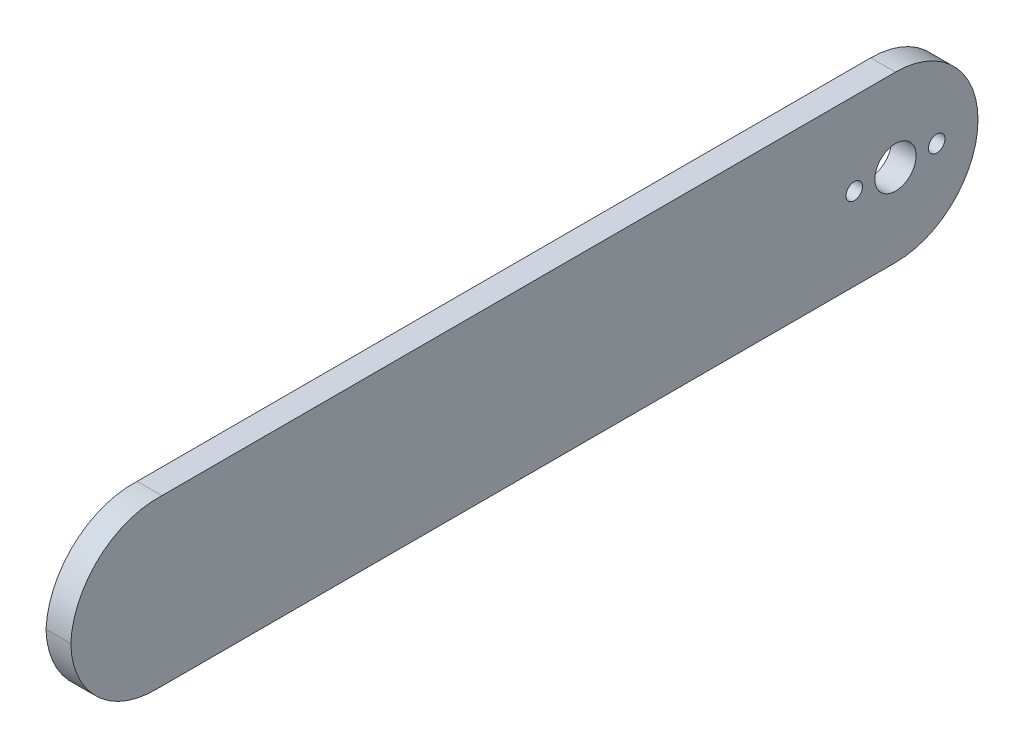
SolidWorks part; units mm, degrees
ref_plane "Front" through (0, 0, 0) normal (0, 0, 1) x (1, 0, 0)
ref_plane "Top" through (0, 0, 0) normal (0, 1, 0) x (1, 0, 0)
ref_plane "Right" through (0, 0, 0) normal (1, 0, 0) x (0, 0, -1)
sketch "Sketch1" plane through (0, 0, 0) normal (1, 0, 0) x (0, 0, -1)
  line L0 (-81.3717, 9.0404) -> (7.5758, 9.0404)
  line L1 (-81.898, -10.9596) -> (7.5758, -10.9596)
  arc A0 (17.5758, -0.9596) -> (7.5758, 9.0404) centre (7.5758, -0.9596) ccw
  arc A1 (7.5758, -10.9596) -> (17.5758, -0.9596) centre (7.5758, -0.9596) ccw
  arc A2 (-92.4242, -0.9596) -> (-81.3717, 9.0404) centre (-81.898, -1.4859) cw
  arc A3 (-81.898, -10.9596) -> (-92.4242, -0.9596) centre (-82.1611, -0.6965) cw
  circle A4 centre (7.5758, -0.9596) radius 2.5
  circle A5 centre (12.5758, -0.9596) radius 1
  circle A6 centre (2.5758, -0.9596) radius 1
  point P7 (17.5758, 9.0404)
  dimension "D3" = 5
  dimension "D1" = 10
  dimension "D4" = 5
  dimension "D2" = 5
  dimension "D5" = 2
  dimension "D6" = 2
extrude "Boss-Extrude1" add sketch "Sketch1" along normal blind 3
